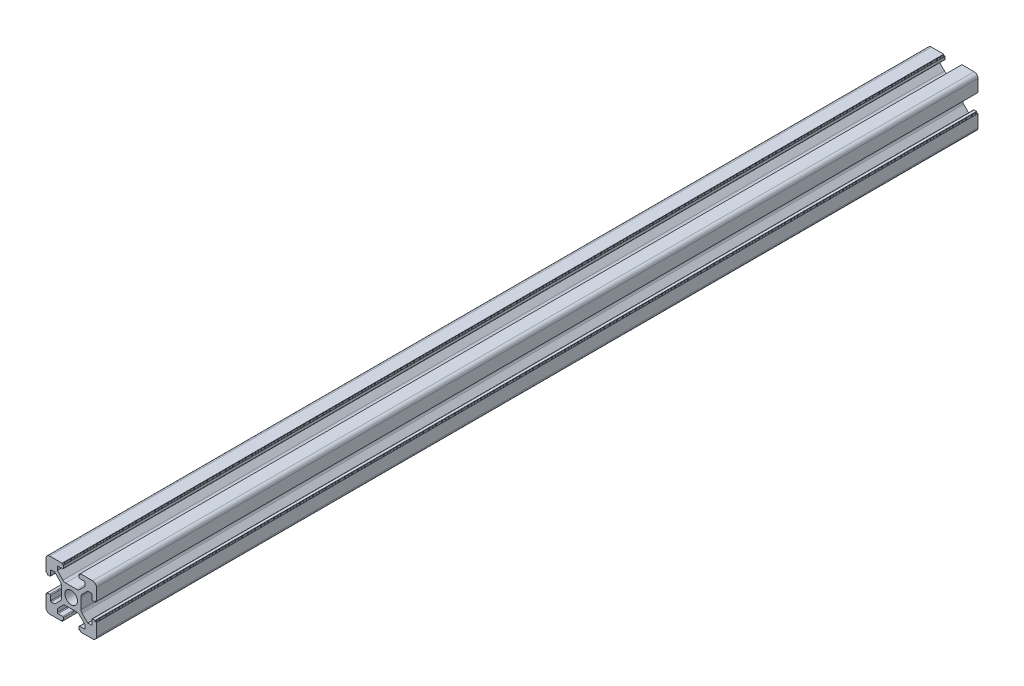
SolidWorks part; units mm, degrees
ref_plane "前视基准面" through (0, 0, 0) normal (0, 0, 1) x (1, 0, 0)
ref_plane "上视基准面" through (0, 0, 0) normal (0, 1, 0) x (1, 0, 0)
ref_plane "右视基准面" through (0, 0, 0) normal (1, 0, 0) x (0, 0, -1)
sketch "草图1" plane through (0, 0, 0) normal (0, 0, 1) x (1, 0, 0)
  line L0 (4.216, 3.2442) -> (6.4367, 5.4649)
  line L1 (6.4367, 5.4649) -> (7.7767, 5.4649)
  line L2 (8.0767, 5.1649) -> (8.0767, 3.3649)
  line L3 (8.3767, 3.0649) -> (9.3767, 3.0649)
  line L4 (9.3767, 3.0649) -> (9.3767, 3.3649)
  line L5 (9.5767, 3.5649) -> (9.8767, 3.5649)
  line L6 (9.8767, 3.5649) -> (9.8767, 8.4649)
  line L7 (8.3767, 9.9649) -> (3.4767, 9.9649)
  line L8 (3.4767, 9.9649) -> (3.4767, 9.6649)
  line L9 (3.2767, 9.4649) -> (2.9767, 9.4649)
  line L10 (2.9767, 9.4649) -> (2.9767, 8.4649)
  line L11 (3.2767, 8.1649) -> (5.0767, 8.1649)
  line L12 (5.3767, 7.8649) -> (5.3767, 6.5249)
  line L13 (5.3767, 6.5249) -> (3.156, 4.3042)
  line L14 (2.0953, 3.8649) -> (-2.342, 3.8649)
  line L15 (-3.4027, 4.3042) -> (-5.6233, 6.5249)
  line L16 (-5.6233, 6.5249) -> (-5.6233, 7.8649)
  line L17 (-5.3233, 8.1649) -> (-3.5233, 8.1649)
  line L18 (-3.2233, 8.4649) -> (-3.2233, 9.4649)
  line L19 (-3.2233, 9.4649) -> (-3.5233, 9.4649)
  line L20 (-3.7233, 9.6649) -> (-3.7233, 9.9649)
  line L21 (-3.7233, 9.9649) -> (-8.6233, 9.9649)
  line L22 (-10.1233, 8.4649) -> (-10.1233, 3.5649)
  line L23 (-10.1233, 3.5649) -> (-9.8233, 3.5649)
  line L24 (-9.6233, 3.3649) -> (-9.6233, 3.0649)
  line L25 (-9.6233, 3.0649) -> (-8.6233, 3.0649)
  line L26 (-8.3233, 3.3649) -> (-8.3233, 5.1649)
  line L27 (-8.0233, 5.4649) -> (-6.6833, 5.4649)
  line L28 (-6.6833, 5.4649) -> (-4.4627, 3.2442)
  line L29 (-4.0233, 2.1836) -> (-4.0233, -2.2538)
  line L30 (-4.4627, -3.3144) -> (-6.6833, -5.5351)
  line L31 (-6.6833, -5.5351) -> (-8.0233, -5.5351)
  line L32 (-8.3233, -5.2351) -> (-8.3233, -3.4351)
  line L33 (-8.6233, -3.1351) -> (-9.6233, -3.1351)
  line L34 (-9.6233, -3.1351) -> (-9.6233, -3.4351)
  line L35 (-9.8233, -3.6351) -> (-10.1233, -3.6351)
  line L36 (-10.1233, -3.6351) -> (-10.1233, -8.5351)
  line L37 (-8.6233, -10.0351) -> (-3.7233, -10.0351)
  line L38 (-3.7233, -10.0351) -> (-3.7233, -9.7351)
  line L39 (-3.5233, -9.5351) -> (-3.2233, -9.5351)
  line L40 (-3.2233, -9.5351) -> (-3.2233, -8.5351)
  line L41 (-3.5233, -8.2351) -> (-5.3233, -8.2351)
  line L42 (-5.6233, -7.9351) -> (-5.6233, -6.5951)
  line L43 (-5.6233, -6.5951) -> (-3.4027, -4.3744)
  line L44 (-2.342, -3.9351) -> (2.0953, -3.9351)
  line L45 (3.156, -4.3744) -> (5.3767, -6.5951)
  line L46 (5.3767, -6.5951) -> (5.3767, -7.9351)
  line L47 (5.0767, -8.2351) -> (3.2767, -8.2351)
  line L48 (2.9767, -8.5351) -> (2.9767, -9.5351)
  line L49 (2.9767, -9.5351) -> (3.2767, -9.5351)
  line L50 (3.4767, -9.7351) -> (3.4767, -10.0351)
  line L51 (3.4767, -10.0351) -> (8.3767, -10.0351)
  line L52 (9.8767, -8.5351) -> (9.8767, -3.6351)
  line L53 (9.8767, -3.6351) -> (9.5767, -3.6351)
  line L54 (9.3767, -3.4351) -> (9.3767, -3.1351)
  line L55 (9.3767, -3.1351) -> (8.3767, -3.1351)
  line L56 (8.0767, -3.4351) -> (8.0767, -5.2351)
  line L57 (7.7767, -5.5351) -> (6.4367, -5.5351)
  line L58 (6.4367, -5.5351) -> (4.216, -3.3144)
  line L59 (3.7767, -2.2538) -> (3.7767, 2.1836)
  circle A0 centre (-0.1233, -0.0351) radius 2.5
  arc A1 (8.0767, 5.1649) -> (7.7767, 5.4649) centre (7.7767, 5.1649) ccw
  arc A2 (8.0767, 3.3649) -> (8.3767, 3.0649) centre (8.3767, 3.3649) ccw
  arc A3 (9.5767, 3.5649) -> (9.3767, 3.3649) centre (9.5767, 3.3649) ccw
  arc A4 (9.8767, 8.4649) -> (8.3767, 9.9649) centre (8.3767, 8.4649) ccw
  arc A5 (3.2767, 9.4649) -> (3.4767, 9.6649) centre (3.2767, 9.6649) ccw
  arc A6 (2.9767, 8.4649) -> (3.2767, 8.1649) centre (3.2767, 8.4649) ccw
  arc A7 (5.3767, 7.8649) -> (5.0767, 8.1649) centre (5.0767, 7.8649) ccw
  arc A8 (2.0953, 3.8649) -> (3.156, 4.3042) centre (2.0953, 5.3649) ccw
  arc A9 (-3.4027, 4.3042) -> (-2.342, 3.8649) centre (-2.342, 5.3649) ccw
  arc A10 (-5.3233, 8.1649) -> (-5.6233, 7.8649) centre (-5.3233, 7.8649) ccw
  arc A11 (-3.5233, 8.1649) -> (-3.2233, 8.4649) centre (-3.5233, 8.4649) ccw
  arc A12 (-3.7233, 9.6649) -> (-3.5233, 9.4649) centre (-3.5233, 9.6649) ccw
  arc A13 (-8.6233, 9.9649) -> (-10.1233, 8.4649) centre (-8.6233, 8.4649) ccw
  arc A14 (-9.6233, 3.3649) -> (-9.8233, 3.5649) centre (-9.8233, 3.3649) ccw
  arc A15 (-8.6233, 3.0649) -> (-8.3233, 3.3649) centre (-8.6233, 3.3649) ccw
  arc A16 (-8.0233, 5.4649) -> (-8.3233, 5.1649) centre (-8.0233, 5.1649) ccw
  arc A17 (-4.0233, 2.1836) -> (-4.4627, 3.2442) centre (-5.5233, 2.1836) ccw
  arc A18 (-4.4627, -3.3144) -> (-4.0233, -2.2538) centre (-5.5233, -2.2538) ccw
  arc A19 (-8.3233, -5.2351) -> (-8.0233, -5.5351) centre (-8.0233, -5.2351) ccw
  arc A20 (-8.3233, -3.4351) -> (-8.6233, -3.1351) centre (-8.6233, -3.4351) ccw
  arc A21 (-9.8233, -3.6351) -> (-9.6233, -3.4351) centre (-9.8233, -3.4351) ccw
  arc A22 (-10.1233, -8.5351) -> (-8.6233, -10.0351) centre (-8.6233, -8.5351) ccw
  arc A23 (-3.5233, -9.5351) -> (-3.7233, -9.7351) centre (-3.5233, -9.7351) ccw
  arc A24 (-3.2233, -8.5351) -> (-3.5233, -8.2351) centre (-3.5233, -8.5351) ccw
  arc A25 (-5.6233, -7.9351) -> (-5.3233, -8.2351) centre (-5.3233, -7.9351) ccw
  arc A26 (-2.342, -3.9351) -> (-3.4027, -4.3744) centre (-2.342, -5.4351) ccw
  arc A27 (3.156, -4.3744) -> (2.0953, -3.9351) centre (2.0953, -5.4351) ccw
  arc A28 (5.0767, -8.2351) -> (5.3767, -7.9351) centre (5.0767, -7.9351) ccw
  arc A29 (3.2767, -8.2351) -> (2.9767, -8.5351) centre (3.2767, -8.5351) ccw
  arc A30 (3.4767, -9.7351) -> (3.2767, -9.5351) centre (3.2767, -9.7351) ccw
  arc A31 (8.3767, -10.0351) -> (9.8767, -8.5351) centre (8.3767, -8.5351) ccw
  arc A32 (9.3767, -3.4351) -> (9.5767, -3.6351) centre (9.5767, -3.4351) ccw
  arc A33 (8.3767, -3.1351) -> (8.0767, -3.4351) centre (8.3767, -3.4351) ccw
  arc A34 (7.7767, -5.5351) -> (8.0767, -5.2351) centre (7.7767, -5.2351) ccw
  arc A35 (3.7767, -2.2538) -> (4.216, -3.3144) centre (5.2767, -2.2538) ccw
  arc A36 (4.216, 3.2442) -> (3.7767, 2.1836) centre (5.2767, 2.1836) ccw
extrude "凸台-拉伸1" add sketch "草图1" along normal blind 350
